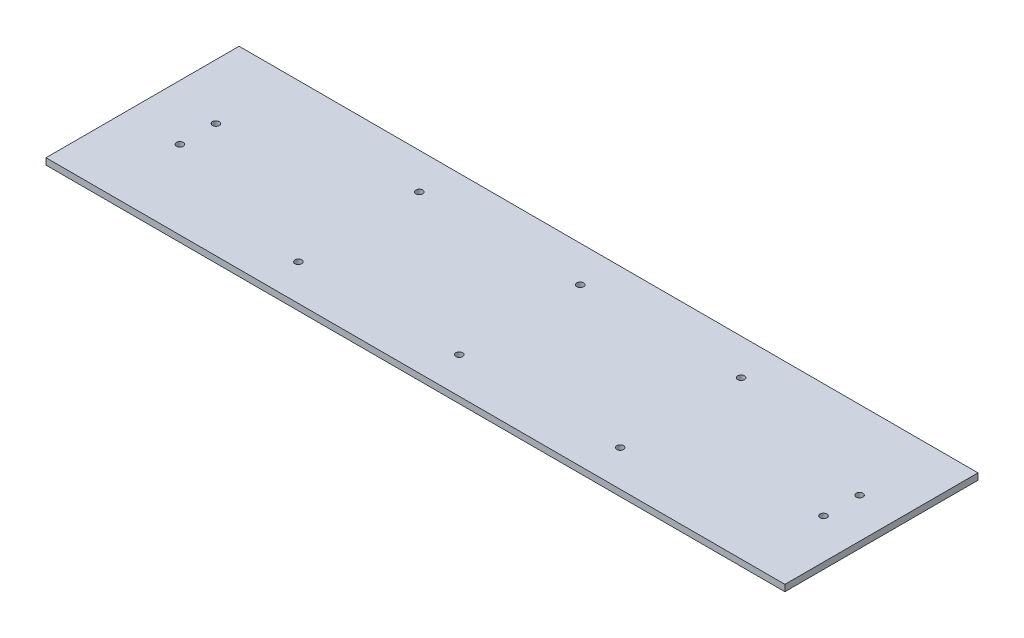
SolidWorks part; units mm, degrees
ref_plane "Front Plane" through (0, 0, 0) normal (0, 0, 1) x (1, 0, 0)
ref_plane "Top Plane" through (0, 0, 0) normal (0, 1, 0) x (1, 0, 0)
ref_plane "Right Plane" through (0, 0, 0) normal (1, 0, 0) x (0, 0, -1)
sketch "Sketch1" plane through (0, 0, 0) normal (0, 1, 0) x (1, 0, 0)
  line L0 (0, 0) -> (0, 150)
  line L1 (0, 150) -> (574, 150)
  line L2 (574, 150) -> (574, 0)
  line L3 (574, 0) -> (0, 0)
  circle A0 centre (43, 61) radius 2.65
  circle A1 centre (168, 28) radius 2.65
  circle A2 centre (293, 28) radius 2.65
  circle A3 centre (418, 28) radius 2.65
  circle A4 centre (543, 61) radius 2.65
  circle A5 centre (543, 89) radius 2.65
  circle A6 centre (418, 122) radius 2.65
  circle A7 centre (293, 122) radius 2.65
  circle A8 centre (168, 122) radius 2.65
  circle A9 centre (43, 89) radius 2.65
  dimension "D9" = 5.3
  dimension "D1" = 574
  dimension "D2" = 150
  dimension "D10" = 125
  dimension "D11" = 125
  dimension "D14" = 125
  dimension "D12" = 125
extrude "Boss-Extrude1" add sketch "Sketch1" along normal blind 5
